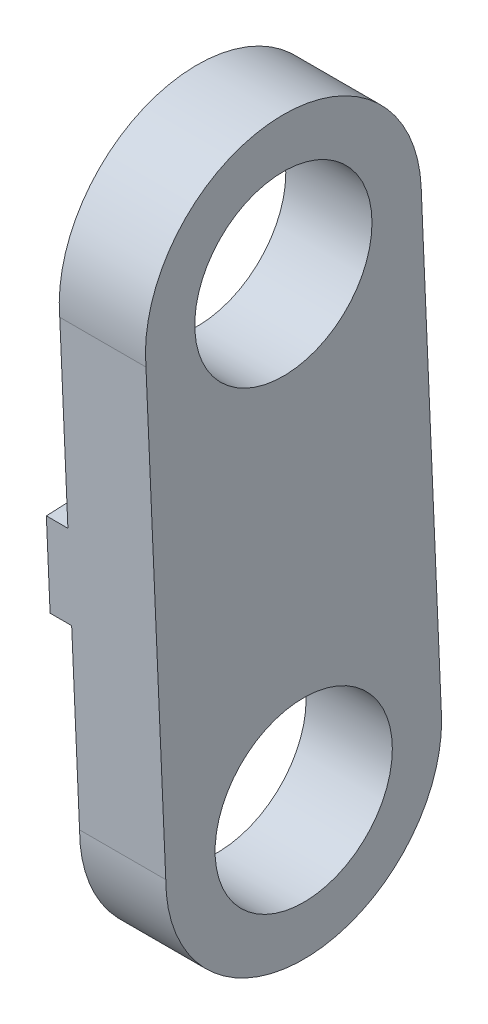
SolidWorks part; units mm, degrees
material "ABS"
ref_plane "Front Plane" through (0, 0, 0) normal (0, 0, 1) x (1, 0, 0)
ref_plane "Top Plane" through (0, 0, 0) normal (0, 1, 0) x (1, 0, 0)
ref_plane "Right Plane" through (0, 0, 0) normal (1, 0, 0) x (0, 0, -1)
sketch "Sketch1" plane through (0, 0, 0) normal (1, 0, 0) x (0, 0, -1)
  line L0 (0, 0) -> (196.85, 0) construction
  line L1 (0, 0) -> (196.1009, 17.1566) construction
  line L2 (191.0403, 16.7139) -> (191.77, 0)
  line L3 (196.1009, 17.1566) -> (187.6937, 16.4211) construction
  line L4 (201.1762, 17.3768) -> (201.93, 0)
  circle A0 centre (196.85, 0) radius 3.2639
  circle A1 centre (196.1009, 17.1566) radius 3.2639
  arc A2 (201.1762, 17.3768) -> (191.0403, 16.7139) centre (196.1009, 17.1566) ccw
  arc A3 (191.77, 0) -> (201.93, 0) centre (196.85, 0) ccw
  dimension "D2" = 6.5278
  dimension "D4" = 6.5278
  dimension "D6" = 10.16
  dimension "D7" = 10.16
  dimension "D1" = 196.85
  dimension "D3" = 5
  dimension "D5" = 196.85
extrude "Boss-Extrude1" add sketch "Sketch1" along normal blind 3.175
sketch "Sketch2" plane through (0, 0, 0) normal (-1, 0, 0) x (0, 0, 1)
  line L0 (-201.5531, 8.6884) -> (-191.4051, 8.3569) construction
  line L1 (-201.93, 0) -> (-201.1762, 17.3768) construction
  line L2 (-191.0403, 16.7139) -> (-191.77, 0) construction
  line L3 (-201.5531, 8.6884) -> (-201.6219, 7.1024)
  line L4 (-201.6219, 7.1024) -> (-191.4792, 6.6595)
  line L5 (-191.4792, 6.6595) -> (-191.3406, 9.8343)
  line L6 (-191.3406, 9.8343) -> (-201.4843, 10.2744)
  line L7 (-201.4843, 10.2744) -> (-201.5531, 8.6884)
  dimension "D1" = 1.5875
extrude "Boss-Extrude2" add sketch "Sketch2" along normal blind 0.7937
